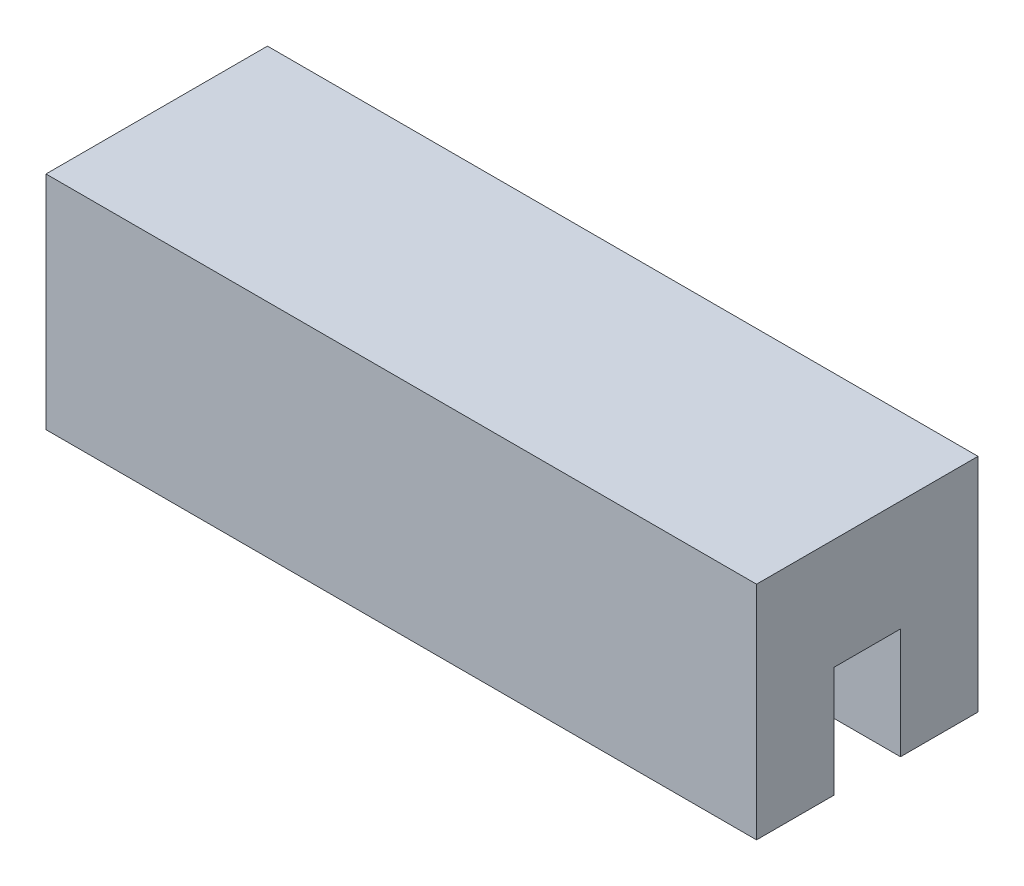
SolidWorks part; units mm, degrees
ref_plane "Front Plane" through (0, 0, 0) normal (0, 0, 1) x (1, 0, 0)
ref_plane "Top Plane" through (0, 0, 0) normal (0, 1, 0) x (1, 0, 0)
ref_plane "Right Plane" through (0, 0, 0) normal (1, 0, 0) x (0, 0, -1)
sketch "Sketch2" plane through (0, 0, 0) normal (1, 0, 0) x (0, 0, -1)
  line L1 (-12, 12) -> (12, 12)
  line L2 (-12, 12) -> (-12, -12)
  line L3 (-12, -12) -> (12, -12)
  line L4 (12, 12) -> (12, -12)
  line L5 (-12, 12) -> (12, -12) construction
  line L6 (-12, -12) -> (12, 12) construction
  point P0 (0, 0)
  dimension "D1" = 24
  dimension "D2" = 24
extrude "Boss-Extrude1" add sketch "Sketch2" along normal blind 77
sketch "Sketch3" plane through (77, 0, 0) normal (1, 0, 0) x (0, 0, -1)
  line L0 (-12, -12) -> (12, -12) construction
  line L1 (0, 0) -> (3.6, 0)
  line L2 (0, 0) -> (0, -12)
  line L3 (0, -12) -> (3.6, -12)
  line L4 (3.6, 0) -> (3.6, -12)
  dimension "D1" = 3.6
extrude "Cut-Extrude3" cut sketch "Sketch3" against normal up to surface (77 mm away) up to face at (0, 0, 0)
mirror "Mirror1" about plane through (0, 0, 0) normal (0, 0, 1) of "Cut-Extrude3"
sketch "Sketch4" plane through (0, 0, -12) normal (0, 0, 1) x (1, 0, 0)
  line L0 (77, -12) -> (0, -12) construction
  line L5 (0, -12) -> (0, 12) construction
  circle A0 centre (40, 2) radius 2.1
  circle A1 centre (22.5, -6) radius 4.5
  circle A2 centre (5, 2) radius 2.1
  dimension "D1" = 4.2
  dimension "D2" = 4.2
  dimension "D7" = 9
  dimension "D8" = 0
  dimension "D9" = 5
  dimension "D4" = 6
  dimension "D3" = 35
  dimension "D5" = 19.2419
  dimension "D6" = 19.2419
extrude "Cut-Extrude4" cut sketch "Sketch4" along normal up to surface (8.4 mm away) up to face at (38.5, -6, -3.6)
equation "\"rail width\"= 24"
equation "\"system width\"= 125"
equation "\"system depth\"= 250"
equation "\"internal height\"= 100"
equation "\"carriage height\"= 24"
equation "\"belt width\"= 6"
equation "\"worm gear diameter\"= 8"
equation "\"D1@Sketch2\"=\"rail width\""
equation "\"D2@Sketch2\"=\"rail width\""
equation "\"D1@Boss-Extrude1\"=\"system width\"-(2*\"rail width\")"
equation "\"D1@Sketch3\"=\"belt width\"*0.6"
